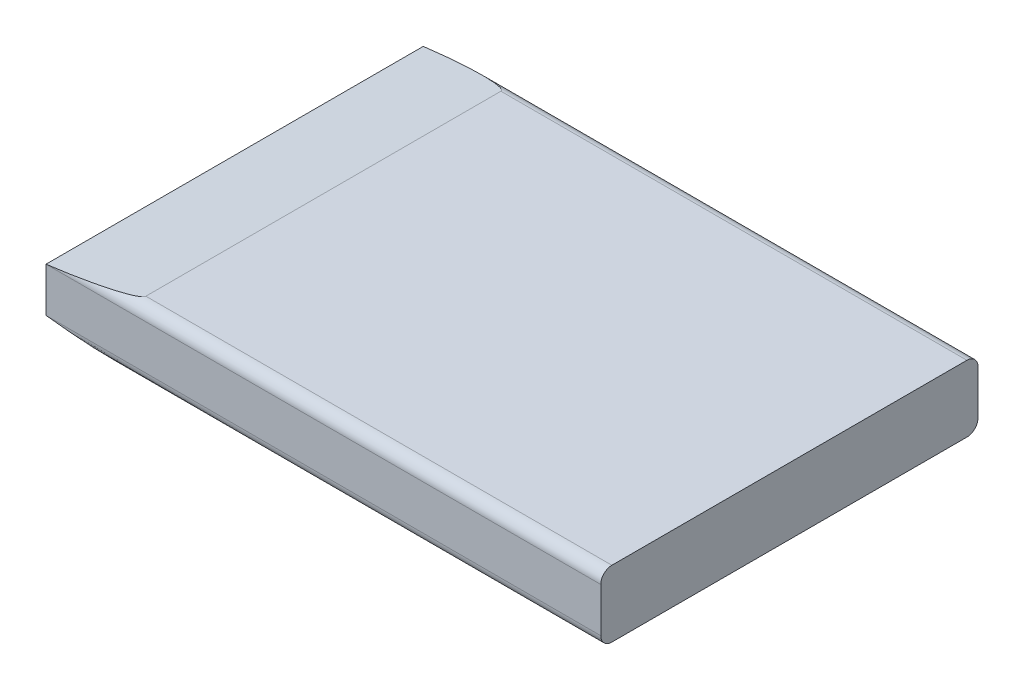
SolidWorks part; units mm, degrees
ref_plane "前视基准面" through (0, 0, 0) normal (0, 0, 1) x (1, 0, 0)
ref_plane "上视基准面" through (0, 0, 0) normal (0, 1, 0) x (1, 0, 0)
ref_plane "右视基准面" through (0, 0, 0) normal (1, 0, 0) x (0, 0, -1)
other "Configuration Table"
sketch "草图1" plane through (0, 0, 0) normal (0, 1, 0) x (1, 0, 0)
  line L1 (-25, -17) -> (25, -17)
  line L2 (-25, -17) -> (-25, 17)
  line L3 (-25, 17) -> (25, 17)
  line L4 (25, -17) -> (25, 17)
  line L5 (-25, -17) -> (25, 17) construction
  line L6 (-25, 17) -> (25, -17) construction
  point P0 (0, 0)
  dimension "D1" = 50
  dimension "D2" = 34
extrude "凸台-拉伸1" add sketch "草图1" along normal blind 6
fillet "圆角1" radius 1 4 edges at (0, 0, 17) (0, 6, 17) (0, 6, -17) (0, 0, -17)
sketch "草图2" plane through (0, 0, 17) normal (0, 0, 1) x (1, 0, 0)
  line L0 (-25, 5) -> (-17, 6)
  line L1 (-25, 5) -> (-25, 1) construction
  line L2 (-25, 6) -> (25, 6) construction
  line L3 (-17, 6) -> (-17, 8)
  line L4 (-17, 8) -> (-27, 8)
  line L5 (-27, 8) -> (-27, -2)
  line L6 (-27, -2) -> (-17, -2)
  line L7 (-17, -2) -> (-17, 0)
  line L8 (25, 0) -> (-25, 0) construction
  line L9 (-17, 0) -> (-25, 1)
  line L10 (-25, 1) -> (-25, 5)
  dimension "D1" = 8
  dimension "D2" = 8
  dimension "D3" = 4
  dimension "D4" = 1
  dimension "D5" = 10
  dimension "D6" = 2
  dimension "D7" = 2
extrude "切除-拉伸1" cut sketch "草图2" against normal blind 40
